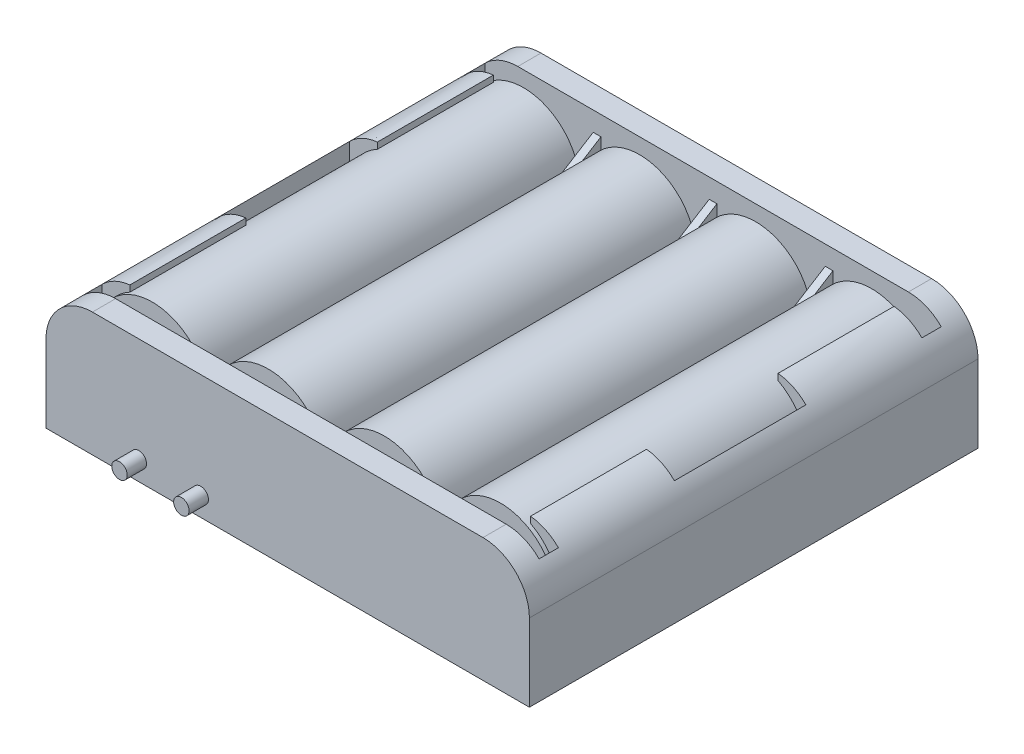
SolidWorks part; units mm, degrees
ref_plane "Front Plane" through (0, 0, 0) normal (0, 0, 1) x (1, 0, 0)
ref_plane "Top Plane" through (0, 0, 0) normal (0, 1, 0) x (1, 0, 0)
ref_plane "Right Plane" through (0, 0, 0) normal (1, 0, 0) x (0, 0, -1)
sketch "Sketch1" plane through (0, 0, 0) normal (0, 1, 0) x (1, 0, 0)
  line L1 (-31.25, -29) -> (31.25, -29)
  line L2 (-31.25, -29) -> (-31.25, 29)
  line L3 (-31.25, 29) -> (31.25, 29)
  line L4 (31.25, -29) -> (31.25, 29)
  line L5 (-31.25, -29) -> (31.25, 29) construction
  line L6 (-31.25, 29) -> (31.25, -29) construction
  point P0 (0, 0)
  dimension "D1" = 62.5
  dimension "D2" = 58
extrude "Boss-Extrude1" add sketch "Sketch1" along normal blind 16
fillet "Fillet1" radius 6 2 edges at (31.25, 16, 0) (-31.25, 16, 0)
sketch "Sketch2" plane through (0, 16, 0) normal (0, 1, 0) x (1, 0, 0)
  line L0 (0, 0) -> (0, 26) construction
  line L1 (-29.5, 26) -> (-15.5, 26)
  line L2 (-29.5, 26) -> (-29.5, 23.5)
  line L3 (-29.5, -26) -> (-15.5, -26)
  line L4 (-15.5, 26) -> (-15.5, -26)
  line L5 (-14.5, 26) -> (-0.5, 26)
  line L6 (-14.5, 26) -> (-14.5, -26)
  line L7 (-14.5, -26) -> (-0.5, -26)
  line L8 (-0.5, 26) -> (-0.5, -26)
  line L9 (15.5, 26) -> (29.5, 26)
  line L10 (15.5, 26) -> (15.5, -26)
  line L11 (15.5, -26) -> (29.5, -26)
  line L12 (29.5, 26) -> (29.5, 23.5)
  line L13 (0, 0) -> (-0.5, 0) construction
  line L14 (29.5, 8.5) -> (25.9, 8.5)
  line L15 (29.5, -23.5) -> (25.9, -23.5)
  line L17 (29.5, -8.5) -> (25.9, -8.5)
  line L18 (25.9, -23.5) -> (25.9, -8.5)
  line L19 (25.9, 23.5) -> (25.9, 8.5)
  line L20 (29.5, 23.5) -> (25.9, 23.5)
  line L23 (-29.5, 23.5) -> (-25.9, 23.5)
  line L24 (-25.9, 23.5) -> (-25.9, 8.5)
  line L25 (-29.5, 8.5) -> (-25.9, 8.5)
  line L26 (-29.5, -8.5) -> (-25.9, -8.5)
  line L27 (-25.9, -23.5) -> (-25.9, -8.5)
  line L28 (-29.5, -23.5) -> (-25.9, -23.5)
  line L30 (-29.5, 8.5) -> (-29.5, -8.5)
  line L31 (-29.5, -23.5) -> (-29.5, -26)
  line L32 (29.5, 8.5) -> (29.5, -8.5)
  line L33 (29.5, -23.5) -> (29.5, -26)
  line L34 (-15.5, -26) -> (-14.5, -26) construction
  line L35 (0.5, 26) -> (14.5, 26)
  line L36 (0.5, 26) -> (0.5, -26)
  line L37 (0.5, -26) -> (14.5, -26)
  line L38 (14.5, 26) -> (14.5, -26)
  line L39 (-0.5, -26) -> (0.5, -26) construction
  dimension "D1" = 14
  dimension "D2" = 52
  dimension "D3" = 1
  dimension "D4" = 3.6
  dimension "D5" = 15
  dimension "D6" = 17
extrude "Cut-Extrude1" cut sketch "Sketch2" against normal blind 14
sketch "Sketch3" plane through (15.5, 0, 0) normal (1, 0, 0) x (0, 0, -1)
  line L0 (-26, 16) -> (-26, 13.5)
  line L1 (-26, 14.2353) -> (-26, 16) construction
  line L2 (-26, 13.5) -> (-17.5, 8.2)
  line L3 (-17.5, 8.2) -> (17.5, 8.2)
  line L4 (0, 0) -> (0, 8.2) construction
  line L5 (-29, 0) -> (29, 0) construction
  line L6 (26, 16) -> (-26, 16) construction
  line L7 (26, 16) -> (26, 13.5)
  line L8 (26, 13.5) -> (17.5, 8.2)
  line L9 (26, 16) -> (-26, 16)
  dimension "D1" = 2.5
  dimension "D2" = 7.8
  dimension "D3" = 8.5
extrude "Cut-Extrude2" cut sketch "Sketch3" against normal up to surface (31 mm away) up to face at (-15.5, 9, 0)
sketch "Sketch4" plane through (0, 0, 0) normal (0, 0, 1) x (1, 0, 0)
  line L0 (-15.5, 2) -> (-29.5, 2) construction
  line L1 (-15.5, 2) -> (-29.5, 2) construction
  line L2 (-0.5, 2) -> (-14.5, 2) construction
  line L3 (-0.5, 2) -> (-14.5, 2) construction
  line L4 (29.5, 2) -> (15.5, 2) construction
  line L5 (29.5, 2) -> (15.5, 2) construction
  line L6 (-25.25, 16) -> (25.25, 16) construction
  line L7 (-22.5, 8.75) -> (-7.5, 8.75) construction
  line L8 (-7.5, 8.75) -> (7.5, 8.75) construction
  line L9 (7.5, 8.75) -> (22.5, 8.75) construction
  circle A0 centre (-22.5, 8.75) radius 7.25
  circle A1 centre (-7.5, 8.75) radius 7.25
  circle A2 centre (22.5, 8.75) radius 7.25
  circle A3 centre (7.5, 8.75) radius 7.25
  point P9 (-22.5, 2)
  point P14 (22.5, 2)
  dimension "D1" = 14.5
extrude "Boss-Extrude3" add sketch "Sketch4" along normal mid plane 48
sketch "Sketch6" plane through (0, 0, 29) normal (0, 0, 1) x (1, 0, 0)
  line L0 (-31.25, 10) -> (-31.25, 0) construction
  line L1 (-31.25, 0) -> (31.25, 0) construction
  circle A0 centre (-19.25, 2.5) radius 1
  circle A1 centre (-11.25, 2.5) radius 1
  dimension "D1" = 2
  dimension "D2" = 12
  dimension "D3" = 8
  dimension "D4" = 2.5
extrude "Boss-Extrude5" add sketch "Sketch6" along normal blind 2.5
